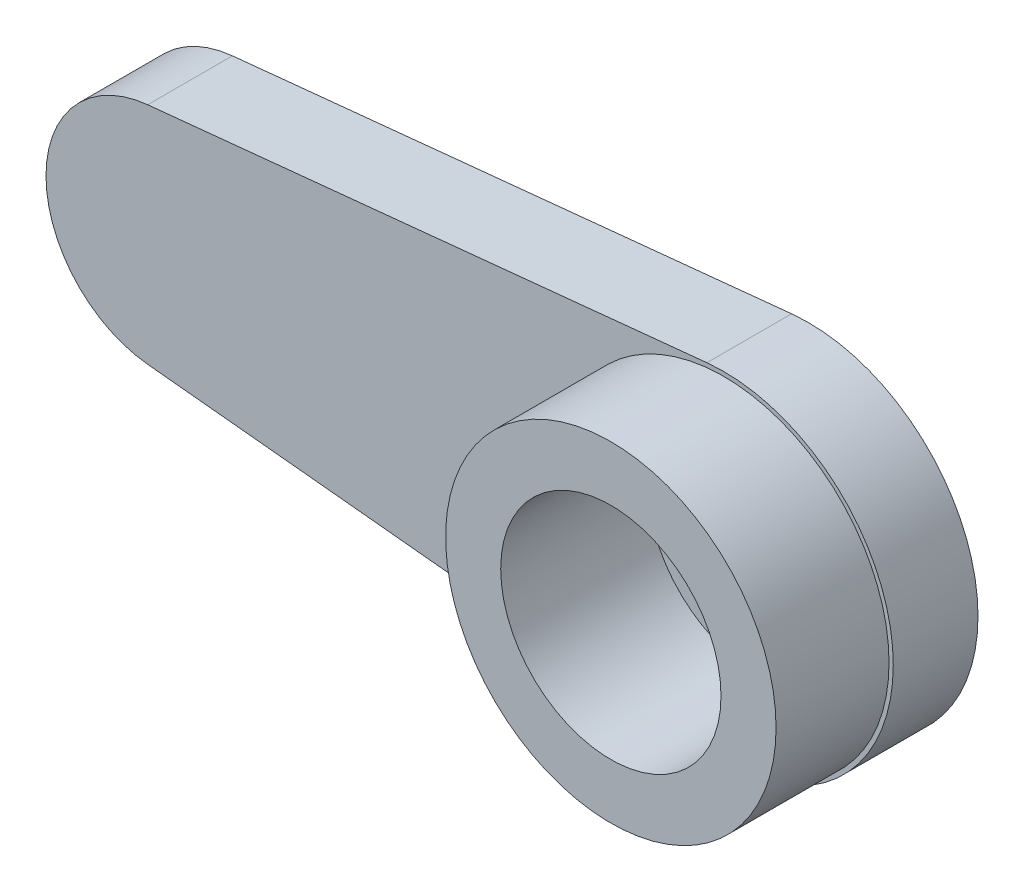
SolidWorks part; units mm, degrees
ref_plane "Plan de face" through (0, 0, 0) normal (0, 0, 1) x (1, 0, 0)
ref_plane "Plan de dessus" through (0, 0, 0) normal (0, 1, 0) x (1, 0, 0)
ref_plane "Plan de droite" through (0, 0, 0) normal (1, 0, 0) x (0, 0, -1)
sketch "Esquisse1" plane through (0, 0, 0) normal (0, 0, 1) x (1, 0, 0)
  line L0 (0, 0) -> (-5.3702, 0) construction
  line L1 (-5.1767, 1.99) -> (4.7233, 2.985)
  line L2 (-5.1767, -1.99) -> (4.7233, -2.985)
  arc A0 (-5.1767, 1.99) -> (-5.1767, -1.99) centre (-4.9767, 0) ccw
  arc A1 (4.7233, -2.985) -> (4.7233, 2.985) centre (5.0233, 0) ccw
  dimension "D1" = 4
  dimension "D2" = 6
  dimension "D3" = 10
extrude "Extrusion1" add sketch "Esquisse1" along normal blind 1.5
sketch "Esquisse2" plane through (0, 0, 1.5) normal (0, 0, 1) x (1, 0, 0)
  circle A0 centre (5.0233, 0) radius 2.925
  arc A1 (4.7233, -2.985) -> (4.7233, 2.985) centre (5.0233, 0) ccw construction
  dimension "D1" = 5.85
extrude "Extrusion2" add sketch "Esquisse2" along normal blind 2
sketch "Esquisse3" plane through (0, 0, 3.5) normal (0, 0, 1) x (1, 0, 0)
  circle A0 centre (5.0233, 0) radius 0.9
  dimension "D1" = 1.8
extrude "Extrusion3" cut sketch "Esquisse3" against normal through all
sketch "Esquisse4" plane through (0, 0, 3.5) normal (0, 0, 1) x (1, 0, 0)
  circle A0 centre (5.0233, 0) radius 1.95
  dimension "D1" = 3.9
extrude "Extrusion4" cut sketch "Esquisse4" against normal blind 2.6
